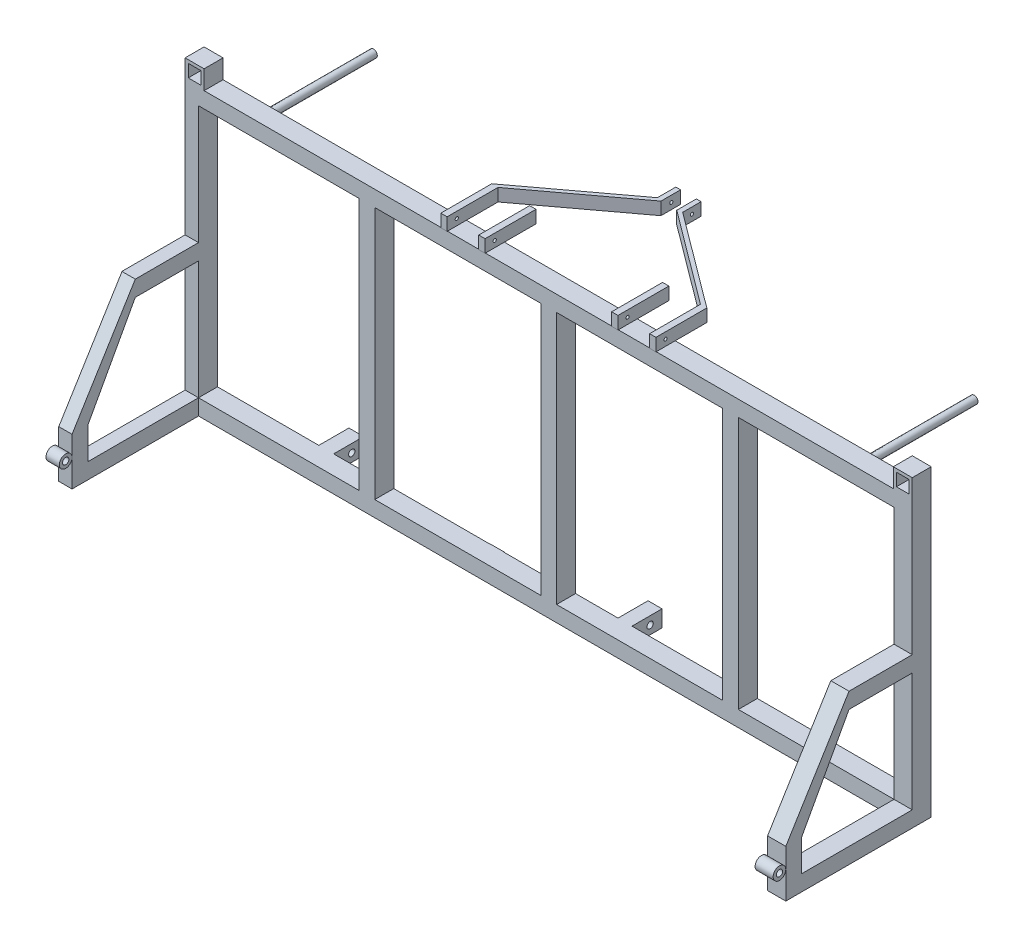
SolidWorks part; units mm, degrees
ref_plane "Front Plane" through (0, 0, 0) normal (0, 0, 1) x (1, 0, 0)
ref_plane "Top Plane" through (0, 0, 0) normal (0, 1, 0) x (1, 0, 0)
ref_plane "Right Plane" through (0, 0, 0) normal (1, 0, 0) x (0, 0, -1)
sketch "Sketch1" plane through (0, 0, 0) normal (0, 0, 1) x (1, 0, 0)
  line L0 (-550, 400) -> (-25, 400)
  line L1 (-1150, -450) -> (1150, -450)
  line L2 (-1150, -450) -> (-1150, 450)
  line L3 (-1150, 450) -> (1150, 450)
  line L4 (1150, -450) -> (1150, 450)
  line L5 (25, 400) -> (550, 400)
  line L6 (600, 400) -> (1092.3896, 400)
  line L7 (-1107.6104, -400) -> (-600, -400)
  line L8 (-1107.6104, -400) -> (-1107.6104, 400)
  line L9 (-1107.6104, 400) -> (-600, 400)
  line L10 (1092.3896, -400) -> (1092.3896, 400)
  line L11 (600, -400) -> (1092.3896, -400)
  line L13 (-600, -400) -> (-600, 400)
  line L15 (-550, -400) -> (-550, 400)
  line L16 (25, -400) -> (550, -400)
  line L17 (-550, -400) -> (-25, -400)
  line L19 (-25, -400) -> (-25, 400)
  line L21 (25, -400) -> (25, 400)
  line L25 (600, -400) -> (600, 400)
  line L27 (550, -400) -> (550, 400)
  point P0 (0, 0)
  point P6 (0, 0)
  point P17 (-575, 0)
  point P22 (0, 0)
  point P27 (575, -6.4314)
  point P32 (550, 0)
  dimension "D1" = 2300
  dimension "D2" = 900
  dimension "D3" = 800
  dimension "D4" = 2200
  dimension "D8" = 50
  dimension "D9" = 50
  dimension "D10" = 50
extrude "Boss-Extrude1" add sketch "Sketch1" along normal blind 60
sketch "Sketch2" plane through (0, 0, 60) normal (0, 0, 1) x (1, 0, 0)
  line L1 (-1107.6104, -400) -> (-1150, -400)
  line L2 (-1107.6104, -400) -> (-1107.6104, -450)
  line L3 (-1107.6104, -450) -> (-1150, -450)
  line L4 (-1150, -400) -> (-1150, -450)
  line L5 (1092.3896, -400) -> (1150, -400)
  line L6 (1092.3896, -400) -> (1092.3896, -450)
  line L7 (1092.3896, -450) -> (1150, -450)
  line L8 (1150, -400) -> (1150, -450)
extrude "Boss-Extrude2" add sketch "Sketch2" along normal blind 1
sketch "Sketch4" plane through (0, 0, 0) normal (0, 0, -1) x (-1, 0, 0)
  line L0 (-25, -400) -> (25, -400)
  line L1 (-25, -400) -> (-25, -450.4636)
  line L2 (25, -400) -> (25, -450.4636)
  line L3 (-25, -450.4636) -> (25, -450.4636)
extrude "Boss-Extrude4" add sketch "Sketch4" along normal blind 1
sketch "Sketch5" plane through (0, 0, 0) normal (0, 0, -1) x (-1, 0, 0)
  line L0 (-25, -400) -> (-550, -400) construction
  line L7 (-1150, -450) -> (-1150, 450) construction
  line L8 (-203.5183, -450) -> (-159.3017, -450)
  line L9 (-203.5183, -450) -> (-203.5183, -400)
  line L10 (-203.5183, -400) -> (-159.3017, -400)
  line L11 (-159.3017, -450) -> (-159.3017, -400)
  point P10 (-181.41, -425)
  dimension "D1" = 968.59
extrude "Boss-Extrude5" add sketch "Sketch5" along normal blind 1
sketch "Sketch6" plane through (0, 0, 0) normal (0, 0, -1) x (-1, 0, 0)
  line L7 (-1150, -450) -> (-1150, 450) construction
  line L8 (202.3661, -450) -> (244.8139, -450)
  line L9 (202.3661, -450) -> (202.3661, -400)
  line L10 (202.3661, -400) -> (244.8139, -400)
  line L11 (244.8139, -450) -> (244.8139, -400)
  point P10 (223.59, -425)
  dimension "D1" = 1373.59
extrude "Boss-Extrude6" add sketch "Sketch6" along normal blind 1
sketch "Sketch7" plane through (0, 0, 0) normal (0, 0, -1) x (-1, 0, 0)
  line L0 (1107.6104, -400) -> (600, -400) construction
  line L1 (740.2047, -400) -> (763.59, -400)
  line L3 (740.2047, -450) -> (763.59, -450)
  line L5 (1150, -450) -> (244.8139, -450) construction
  line L7 (1150, 450) -> (1150, -450) construction
  line L9 (740.2047, -450) -> (740.2047, -400)
  line L11 (786.9753, -450) -> (786.9753, -400)
  line L12 (763.59, -400) -> (786.9753, -400)
  line L13 (763.59, -450) -> (786.9753, -450)
  point P11 (763.59, -425)
  dimension "D1" = 386.41
extrude "Boss-Extrude7" add sketch "Sketch7" along normal blind 1
sketch "Sketch8" plane through (0, 0, 0) normal (0, 0, -1) x (-1, 0, 0)
  line L0 (0, 0) -> (0, 774.7089) construction
  line L1 (-330.2, 776.0795) -> (-330.2, -52.5404) construction
  line L2 (330.2, 825.7434) -> (330.2, -36.1236) construction
  line L3 (-1150, 450) -> (1150, 450) construction
  line L4 (-340.2, 490) -> (-320.2, 490)
  line L5 (-340.2, 490) -> (-340.2, 450)
  line L6 (-340.2, 450) -> (-320.2, 450)
  line L7 (-320.2, 490) -> (-320.2, 450)
  line L8 (220.2, 490) -> (200.2, 490)
  line L9 (320.2, 490) -> (340.2, 490)
  line L10 (320.2, 490) -> (320.2, 450)
  line L11 (320.2, 450) -> (340.2, 450)
  line L12 (340.2, 490) -> (340.2, 450)
  line L13 (220.2, 490) -> (220.2, 450)
  line L14 (220.2, 450) -> (200.2, 450)
  line L15 (200.2, 490) -> (200.2, 450)
  line L16 (-220.2, 490) -> (-200.2, 490)
  line L17 (-220.2, 490) -> (-220.2, 450)
  line L18 (-220.2, 450) -> (-200.2, 450)
  line L19 (-200.2, 490) -> (-200.2, 450)
  point P7 (-330.2, 465)
  point P14 (330.2, 470)
  dimension "D1" = 330.2
  dimension "D2" = 330.2
  dimension "D3" = 20
  dimension "D4" = 40
  dimension "D5" = 40
  dimension "D6" = 20
  dimension "D7" = 100
  dimension "D8" = 40
  dimension "D9" = 100
extrude "Boss-Extrude9" add sketch "Sketch8" against normal through all and the other way blind 100
sketch "Sketch9" plane through (340.2, 0, 0) normal (1, 0, 0) x (0, 0, -1)
  line L0 (-30.5, 496.1683) -> (-30.5, 443.3268) construction
  line L1 (100, 469.7476) -> (-69.9799, 469.7476) construction
  line L2 (100, 490) -> (100, 450) construction
  circle A0 centre (-30.5, 469.7476) radius 5
  point P6 (-30.5, 469.7476)
extrude "Cut-Extrude1" cut sketch "Sketch9" against normal blind 810
sketch "Sketch11" plane through (0, 490, 0) normal (0, 1, 0) x (1, 0, 0)
  line L0 (-568.3509, 351.1) -> (-25, 351.1) construction
  line L1 (-1150, -60) -> (-1150, 0) construction
  line L2 (-1150, -30) -> (427.2422, -30) construction
  line L3 (0, 0) -> (0, 460.6372) construction
  line L4 (340.2, 100) -> (40, 323.828)
  line L5 (-25, 351.1) -> (-25, 320.1)
  line L6 (-25, 351.1) -> (-25, 382.1)
  line L7 (-25, 320.1) -> (-320.2, 100)
  line L8 (-320.2, 100) -> (-340.2, 100)
  line L9 (-25, 382.1) -> (-40, 382.1)
  line L10 (-40, 382.1) -> (-40, 351.1)
  line L11 (-320.2, 100) -> (-220.2, 100) construction
  line L12 (-340.2, 100) -> (-40, 323.828)
  line L13 (-40, 351.1) -> (-40, 323.828)
  line L14 (25, 320.1) -> (320.2, 100)
  line L15 (320.2, 100) -> (340.2, 100)
  line L16 (40, 351.1) -> (40, 323.828)
  line L17 (40, 382.1) -> (40, 351.1)
  line L18 (25, 382.1) -> (40, 382.1)
  line L19 (25, 351.1) -> (25, 382.1)
  line L20 (25, 351.1) -> (25, 320.1)
  point P13 (-12.5, 351.1)
  point P30 (12.5, 351.1)
  dimension "D1" = 381.1
  dimension "D3" = 31
  dimension "D4" = 31
  dimension "D5" = 15
  dimension "D6" = 36.708
  dimension "D7" = 36.708
extrude "Boss-Extrude10" add sketch "Sketch11" against normal blind 40
sketch "Sketch12" plane through (-40, 0, 0) normal (-1, 0, 0) x (0, 0, 1)
  circle A0 centre (-352.964, 470) radius 5
extrude "Cut-Extrude2" cut sketch "Sketch12" against normal blind 179
sketch "Sketch13" plane through (0, 0, 0) normal (0, 0, -1) x (-1, 0, 0)
  line L2 (-203.5183, -400) -> (-159.3017, -400)
  line L3 (-203.5183, -400) -> (-203.5183, -452.386)
  line L4 (-159.3017, -400) -> (-159.3017, -452.386)
  line L6 (-203.5183, -452.386) -> (-159.3017, -452.386)
  line L8 (740.2047, -400) -> (786.9753, -400)
  line L9 (740.2047, -400) -> (740.2047, -451.9253)
  line L10 (786.9753, -400) -> (786.9753, -451.9253)
  line L11 (740.2047, -451.9253) -> (786.9753, -451.9253)
extrude "Boss-Extrude12" add sketch "Sketch13" along normal blind 95
sketch "Sketch14" plane through (-786.9753, 0, 0) normal (-1, 0, 0) x (0, 0, 1)
  circle A0 centre (-57.324, -425.9627) radius 10
  dimension "D1" = 20
extrude "Cut-Extrude3" cut sketch "Sketch14" against normal blind 1270
sketch "Sketch15" plane through (0, 0, 60) normal (0, 0, 1) x (1, 0, 0)
  line L1 (-1150, 450) -> (-1090, 450)
  line L2 (-1150, 450) -> (-1150, 510)
  line L3 (-1150, 510) -> (-1090, 510)
  line L4 (-1090, 450) -> (-1090, 510)
  line L5 (1150, 450) -> (1090, 450)
  line L6 (1150, 450) -> (1150, 510)
  line L7 (1150, 510) -> (1090, 510)
  line L8 (1090, 450) -> (1090, 510)
  line L9 (-1140, 500) -> (-1100, 500)
  line L10 (-1140, 500) -> (-1140, 460)
  line L11 (-1140, 460) -> (-1100, 460)
  line L12 (-1100, 500) -> (-1100, 460)
  line L13 (1100, 500) -> (1140, 500)
  line L14 (1100, 500) -> (1100, 460)
  line L15 (1100, 460) -> (1140, 460)
  line L16 (1140, 500) -> (1140, 460)
  dimension "D1" = 60
  dimension "D2" = 60
  dimension "D3" = 60
  dimension "D4" = 60
  dimension "D5" = 10
  dimension "D6" = 10
  dimension "D7" = 10
  dimension "D8" = 10
  dimension "D9" = 10
  dimension "D10" = 10
  dimension "D11" = 10
  dimension "D12" = 10
extrude "Boss-Extrude13" add sketch "Sketch15" against normal up to vertex
sketch "Sketch16" plane through (0, 0, 0) normal (0, 0, -1) x (-1, 0, 0)
  line L0 (-1150, -450) -> (-1150, 510) construction
  line L1 (1150, 510) -> (1150, -450) construction
  circle A0 centre (-950, 425.8682) radius 12
  circle A1 centre (950, 423.9911) radius 12
  dimension "D1" = 24
  dimension "D2" = 24
  dimension "D3" = 200
  dimension "D4" = 200
extrude "Boss-Extrude14" add sketch "Sketch16" along normal blind 336
sketch "Sketch17" plane through (0, 0, 60) normal (0, 0, 1) x (1, 0, 0)
  line L1 (-1150, -400) -> (-1107.6104, -400)
  line L2 (-1150, -400) -> (-1150, -450)
  line L3 (-1150, -450) -> (-1107.6104, -450)
  line L4 (-1107.6104, -400) -> (-1107.6104, -450)
  line L5 (1092.3896, -400) -> (1150, -400)
  line L6 (1092.3896, -400) -> (1092.3896, -450)
  line L7 (1092.3896, -450) -> (1150, -450)
  line L8 (1150, -400) -> (1150, -450)
extrude "Boss-Extrude15" add sketch "Sketch17" along normal blind 400
sketch "Sketch18" plane through (0, 0, 60) normal (0, 0, 1) x (1, 0, 0)
  line L11 (-1107.6104, 400) -> (-1107.6104, -400) construction
  line L12 (-1150, -25) -> (-1107.6104, -25)
  line L13 (-1150, -25) -> (-1150, 25)
  line L14 (-1150, 25) -> (-1107.6104, 25)
  line L15 (-1107.6104, -25) -> (-1107.6104, 25)
  line L18 (1150, -400) -> (1150, 510) construction
  line L19 (1092.3896, 25) -> (1150, 25)
  line L20 (1092.3896, 25) -> (1092.3896, -25)
  line L21 (1092.3896, -25) -> (1150, -25)
  line L22 (1150, 25) -> (1150, -25)
  line L29 (-1150, 510) -> (-1150, -400) construction
  line L30 (1092.3896, -400) -> (1092.3896, 400) construction
  point P3 (-1128.8052, 0)
  point P10 (1121.1948, 0)
  dimension "D1" = 50
  dimension "D2" = 50
extrude "Boss-Extrude16" add sketch "Sketch18" along normal blind 200
sketch "Sketch19" plane through (-1150, 0, 0) normal (-1, 0, 0) x (0, 0, 1)
  line L0 (460, -400) -> (410, -400)
  line L1 (460, -400) -> (460, -300)
  line L2 (410, -400) -> (410, -300)
  line L3 (460, -300) -> (410, -300)
  line L4 (460, -400) -> (60, -400) construction
  dimension "D1" = 100
  dimension "D2" = 50
extrude "Boss-Extrude17" add sketch "Sketch19" against normal up to vertex (42.3896 mm away) up to point (-1107.6104, -450, 460)
sketch "Sketch20" plane through (-1107.6104, 0, 0) normal (1, 0, 0) x (0, 0, -1)
  line L0 (-260, -25) -> (-410, -300)
  line L1 (-260, 25) -> (-460, -300)
  line L2 (-460, -300) -> (-410, -300)
  line L3 (-260, 25) -> (-260, -25)
extrude "Boss-Extrude18" add sketch "Sketch20" against normal blind 42
sketch "Sketch22" plane through (1150, 0, 0) normal (1, 0, 0) x (0, 0, -1)
  line L0 (-460, -300) -> (-260, 25)
  line L1 (-260, 25) -> (-260, -25)
  line L2 (-260, -25) -> (-410, -300)
  line L4 (-410, -300) -> (-410, -400)
  line L5 (-410, -400) -> (-460, -400)
  line L6 (-460, -400) -> (-460, -300)
extrude "Boss-Extrude19" add sketch "Sketch22" against normal up to vertex
sketch "Sketch25" plane through (-1150, 0, 0) normal (-1, 0, 0) x (0, 0, 1)
  line L0 (460, -300) -> (460, -450) construction
  circle A0 centre (480, -363.3811) radius 20
  circle A1 centre (480, -363.3811) radius 10
extrude "Boss-Extrude20" add sketch "Sketch25" against normal up to vertex (42.3896 mm away) separate body
sketch "Sketch26" plane through (1150, 0, 0) normal (1, 0, 0) x (0, 0, -1)
  circle A0 centre (-480, -363.3811) radius 20
  circle A1 centre (-480, -363.3811) radius 10
  dimension "D1" = 20
extrude "Boss-Extrude21" add sketch "Sketch26" against normal blind 57 separate body
